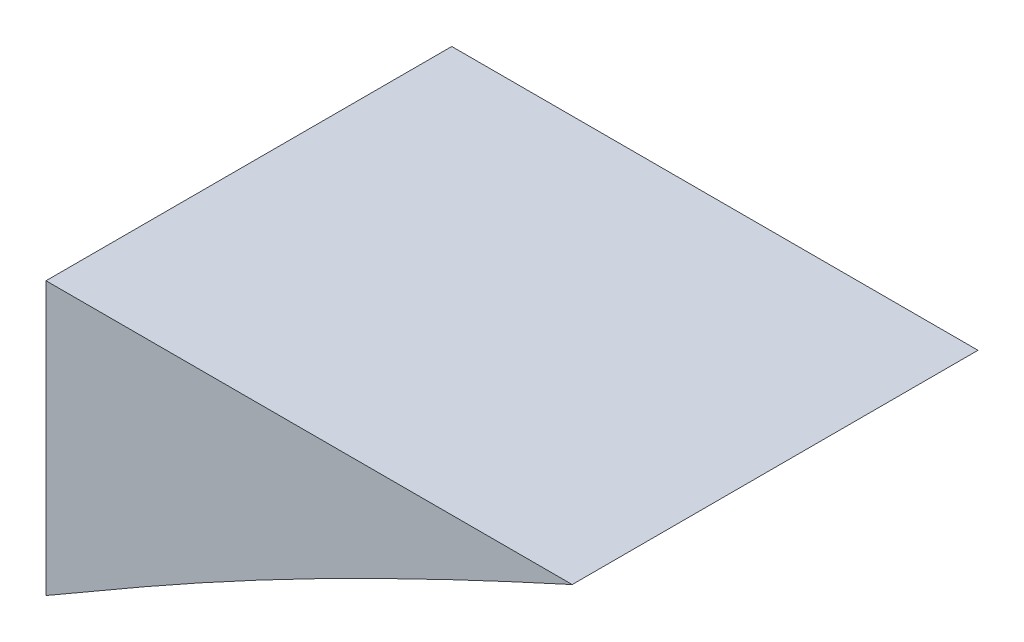
SolidWorks part; units mm, degrees
ref_plane "Front Plane" through (0, 0, 0) normal (0, 0, 1) x (1, 0, 0)
ref_plane "Top Plane" through (0, 0, 0) normal (0, 1, 0) x (1, 0, 0)
ref_plane "Right Plane" through (0, 0, 0) normal (1, 0, 0) x (0, 0, -1)
ref_plane "plane:profile" through (0, 0, 0) normal (0, 0, 1) x (1, 0, 0)
sketch "profile:cubic" plane through (0, 0, 0) normal (0, 0, 1) x (1, 0, 0)
  line L0 (20, 10) -> (0, 10)
  line L1 (0, 10) -> (0, 0)
  spline S0 degree 3 poles (0, 0) (10, 4) (9, 5) (20, 10) knots 0 0 0 0 1 1 1 1
extrude "feature:prism" add sketch "profile:cubic" along normal blind 8 separate body
sketch "profile:cut" plane through (0, 0, 0) normal (0, 0, 1) x (1, 0, 0)
  line L0 (-2, -2) -> (9.625, -2)
  line L1 (9.625, -2) -> (9.625, 12)
  line L2 (9.625, 12) -> (-2, 12)
  line L3 (-2, 12) -> (-2, -2)
extrude "feature:trim" cut sketch "profile:cut" along normal through all
